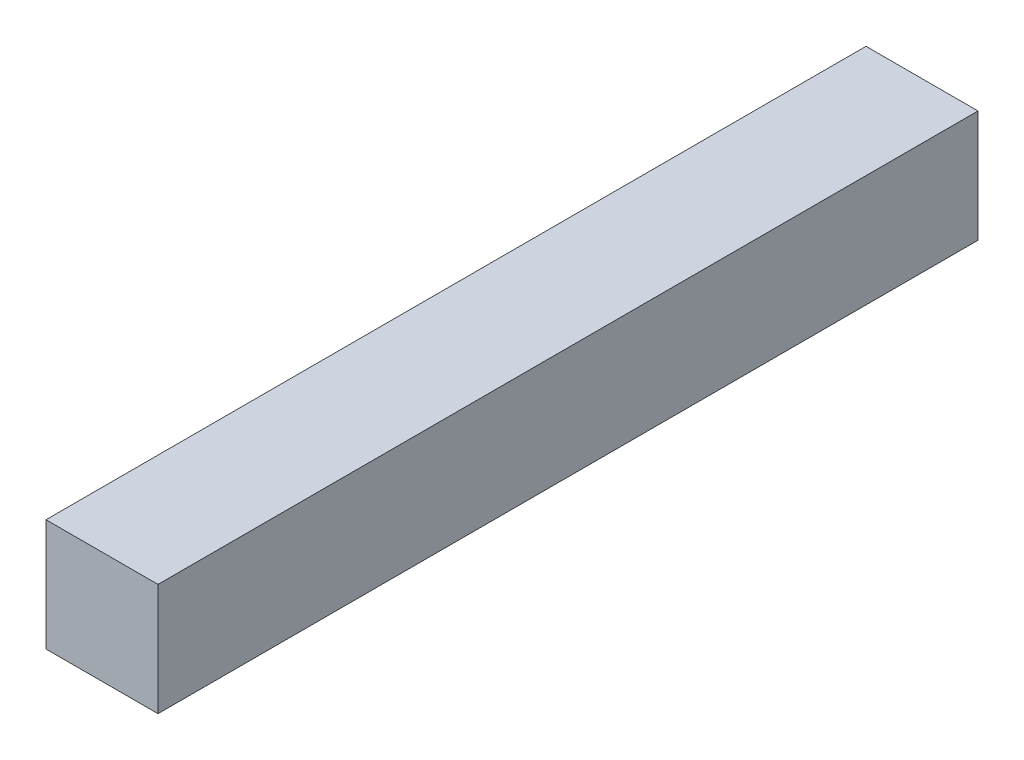
SolidWorks part; units mm, degrees
ref_plane "Płaszczyzna przednia" through (0, 0, 0) normal (0, 0, 1) x (1, 0, 0)
ref_plane "Płaszczyzna górna" through (0, 0, 0) normal (0, 1, 0) x (1, 0, 0)
ref_plane "Płaszczyzna prawa" through (0, 0, 0) normal (1, 0, 0) x (0, 0, -1)
sketch "Szkic1" plane through (0, 0, 0) normal (0, 0, 1) x (1, 0, 0)
  line L1 (-2.39, 2.39) -> (2.39, 2.39)
  line L2 (-2.39, 2.39) -> (-2.39, -2.39)
  line L3 (-2.39, -2.39) -> (2.39, -2.39)
  line L4 (2.39, 2.39) -> (2.39, -2.39)
  point P4 (0, -2.39)
  point P5 (-2.39, 0)
  dimension "D1" = 4.78
  dimension "D2" = 4.78
extrude "Dodanie-wyciągnięcie1" add sketch "Szkic1" along normal blind 35 contours L3 L4 L1 L2
